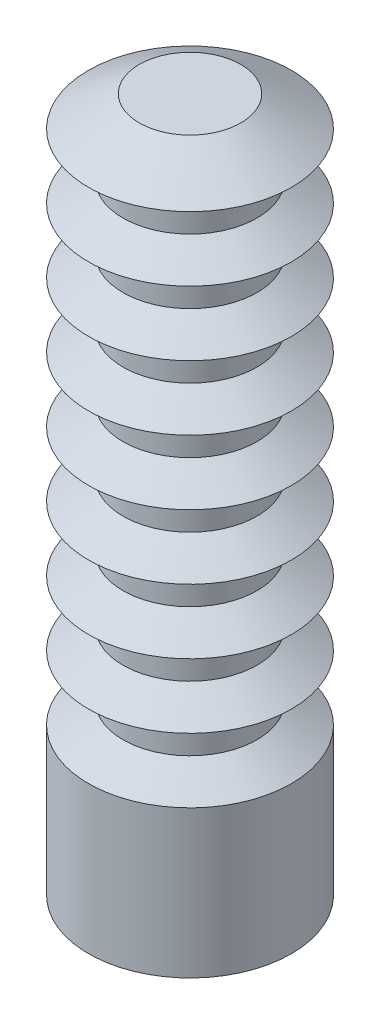
SolidWorks part; units mm, degrees
ref_plane "Front Plane" through (0, 0, 0) normal (0, 0, 1) x (1, 0, 0)
ref_plane "Top Plane" through (0, 0, 0) normal (0, 1, 0) x (1, 0, 0)
ref_plane "Right Plane" through (0, 0, 0) normal (1, 0, 0) x (0, 0, -1)
sketch "Sketch1" plane through (0, 0, 0) normal (0, 0, 1) x (1, 0, 0)
  line L0 (-2.9316, 34.2) -> (-2.9316, 31.2) construction
  line L1 (-0.4316, 32.7) -> (-2.1316, 31.68)
  line L2 (-5.4316, 34.2) -> (-5.4316, 0) construction
  line L3 (-2.1316, 31.68) -> (-2.1316, 30.54)
  line L4 (-2.9316, 34.2) -> (-0.4316, 32.7)
  line L5 (-3.1389, 32.0142) -> (-1.9958, 32.7)
  line L6 (-2.9316, 34.2) -> (-5.4316, 34.2)
  line L7 (-5.4316, 33.4) -> (-3.1389, 33.4)
  line L9 (-2.6564, 33.1045) -> (-3.1389, 33.4)
  line L10 (-3.1389, 33.4) -> (-1.9958, 32.7)
  line L12 (-3.1389, 28.8342) -> (-1.9958, 29.52)
  line L13 (-3.1389, 25.6542) -> (-1.9958, 26.34)
  line L14 (-3.1389, 30.22) -> (-3.1389, 32.0142)
  line L15 (-3.1389, 22.4742) -> (-1.9958, 23.16)
  line L16 (-2.1316, 30.54) -> (-0.4316, 29.52)
  line L17 (-3.1389, 19.2942) -> (-1.9958, 19.98)
  line L18 (-3.1389, 30.22) -> (-1.9958, 29.52)
  line L19 (-0.4316, 29.52) -> (-2.1316, 28.5)
  line L20 (-3.1389, 16.1142) -> (-1.9958, 16.8)
  line L21 (-2.1316, 28.5) -> (-2.1316, 27.36)
  line L22 (-3.1389, 27.04) -> (-3.1389, 28.8342)
  line L23 (-2.1316, 27.36) -> (-0.4316, 26.34)
  line L24 (-3.1389, 27.04) -> (-1.9958, 26.34)
  line L25 (-0.4316, 26.34) -> (-2.1316, 25.32)
  line L26 (-3.1389, 12.9342) -> (-1.9958, 13.62)
  line L27 (-2.1316, 25.32) -> (-2.1316, 24.18)
  line L28 (-3.1389, 23.86) -> (-3.1389, 25.6542)
  line L29 (-2.9316, 34.2) -> (-2.9316, 30.7) construction
  line L30 (-5.4316, 34.2) -> (-5.4316, 33.4)
  line L31 (-2.1316, 24.18) -> (-0.4316, 23.16)
  line L32 (-3.1389, 9.7542) -> (-1.9958, 10.44)
  line L33 (-3.1389, 23.86) -> (-1.9958, 23.16)
  line L35 (-0.4316, 23.16) -> (-2.1316, 22.14)
  line L37 (-2.1316, 22.14) -> (-2.1316, 21)
  line L38 (-3.1389, 20.68) -> (-3.1389, 22.4742)
  line L39 (-2.1316, 21) -> (-0.4316, 19.98)
  line L40 (-3.1389, 20.68) -> (-1.9958, 19.98)
  line L41 (-0.4316, 19.98) -> (-2.1316, 18.96)
  line L43 (-2.1316, 18.96) -> (-2.1316, 17.82)
  line L44 (-3.1389, 17.5) -> (-3.1389, 19.2942)
  line L45 (-2.1316, 17.82) -> (-0.4316, 16.8)
  line L46 (-3.1389, 17.5) -> (-1.9958, 16.8)
  line L47 (-0.4316, 16.8) -> (-2.1316, 15.78)
  line L49 (-2.1316, 15.78) -> (-2.1316, 14.64)
  line L50 (-3.1389, 14.32) -> (-3.1389, 16.1142)
  line L51 (-2.1316, 14.64) -> (-0.4316, 13.62)
  line L52 (-3.1389, 14.32) -> (-1.9958, 13.62)
  line L53 (-0.4316, 13.62) -> (-2.1316, 12.6)
  line L55 (-2.1316, 12.6) -> (-2.1316, 11.46)
  line L56 (-3.1389, 11.14) -> (-3.1389, 12.9342)
  line L57 (-2.1316, 11.46) -> (-0.4316, 10.44)
  line L58 (-3.1389, 11.14) -> (-1.9958, 10.44)
  line L59 (-0.4316, 10.44) -> (-2.1316, 9.42)
  line L60 (-1.9958, 10.44) -> (-3.1543, 9.7449)
  line L61 (-2.1316, 9.42) -> (-2.1316, 8.28)
  line L62 (-3.1389, 7.96) -> (-3.1389, 9.7542)
  line L63 (-2.9316, 31.02) -> (-0.4316, 29.52) [skipped]
  line L64 (-2.1316, 8.28) -> (-0.4316, 7.26)
  line L65 (-2.9316, 27.84) -> (-0.4316, 26.34) [skipped]
  line L66 (-2.9316, 24.66) -> (-0.4316, 23.16) [skipped]
  line L67 (-2.9316, 21.48) -> (-0.4316, 19.98) [skipped]
  line L68 (-2.9316, 18.3) -> (-0.4316, 16.8) [skipped]
  line L69 (-2.9316, 15.12) -> (-0.4316, 13.62) [skipped]
  line L70 (-2.9316, 11.94) -> (-0.4316, 10.44) [skipped]
  line L71 (-3.1389, 7.96) -> (-1.9958, 7.26)
  line L73 (-0.4316, 7.26) -> (-0.4316, 0)
  line L74 (-0.4316, 0) -> (-1.2316, 0)
  line L75 (-1.2316, 0) -> (-1.2316, 6.796)
  line L76 (-1.9958, 7.26) -> (-1.2316, 6.796)
  point P9 (-2.9316, 32.7)
  dimension "D4" = 3.5
  dimension "D2" = 3
  dimension "D3" = 2.5
  dimension "D6" = 0.8
  dimension "D10" = 0.8
  dimension "D9" = 8
revolve "Revolve6" add sketch "Sketch1" angle 360 about L2
